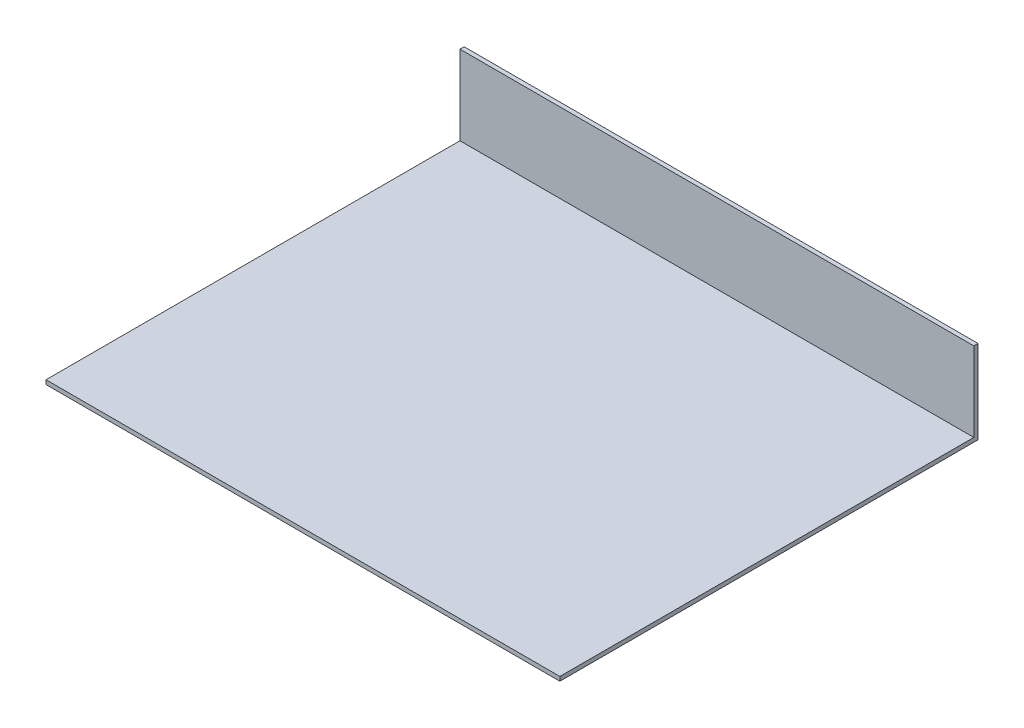
SolidWorks part; units mm, degrees
ref_plane "Front Plane" through (0, 0, 0) normal (0, 0, 1) x (1, 0, 0)
ref_plane "Top Plane" through (0, 0, 0) normal (0, 1, 0) x (1, 0, 0)
ref_plane "Right Plane" through (0, 0, 0) normal (1, 0, 0) x (0, 0, -1)
sketch "Sketch2" plane through (0, 0, 0) normal (0, 1, 0) x (1, 0, 0)
  line L1 (-184.345, 150) -> (184.345, 150)
  line L2 (-184.345, 150) -> (-184.345, -150)
  line L3 (-184.345, -150) -> (184.345, -150)
  line L4 (184.345, 150) -> (184.345, -150)
  line L5 (-184.345, 150) -> (184.345, -150) construction
  line L6 (-184.345, -150) -> (184.345, 150) construction
  point P0 (0, 0)
  dimension "D1" = 300
  dimension "D2" = 368.69
extrude "Boss-Extrude1" add sketch "Sketch2" along normal blind 3
sketch "Sketch3" plane through (0, 3, 0) normal (0, 1, 0) x (1, 0, 0)
  line L0 (184.345, -150) -> (184.345, 150) construction
  line L1 (-184.345, 150) -> (184.345, 150)
  line L2 (-184.345, 150) -> (-184.345, 147)
  line L3 (-184.345, 147) -> (184.345, 147)
  line L4 (184.345, 150) -> (184.345, 147)
  dimension "D1" = 3
extrude "Boss-Extrude2" add sketch "Sketch3" along normal blind 56.91
sketch "Base Plate Placement" plane through (0, 3, 0) normal (0, 1, 0) x (1, 0, 0)
  line L1 (-100, -100) -> (100, -100)
  line L2 (-100, -100) -> (-100, 100)
  line L3 (-100, 100) -> (100, 100)
  line L4 (100, -100) -> (100, 100)
  line L5 (-100, -100) -> (100, 100) construction
  line L6 (-100, 100) -> (100, -100) construction
  circle A0 centre (0, 0) radius 51.65
  point P0 (0, 0)
  dimension "D2" = 103.3
  dimension "D1" = 200
